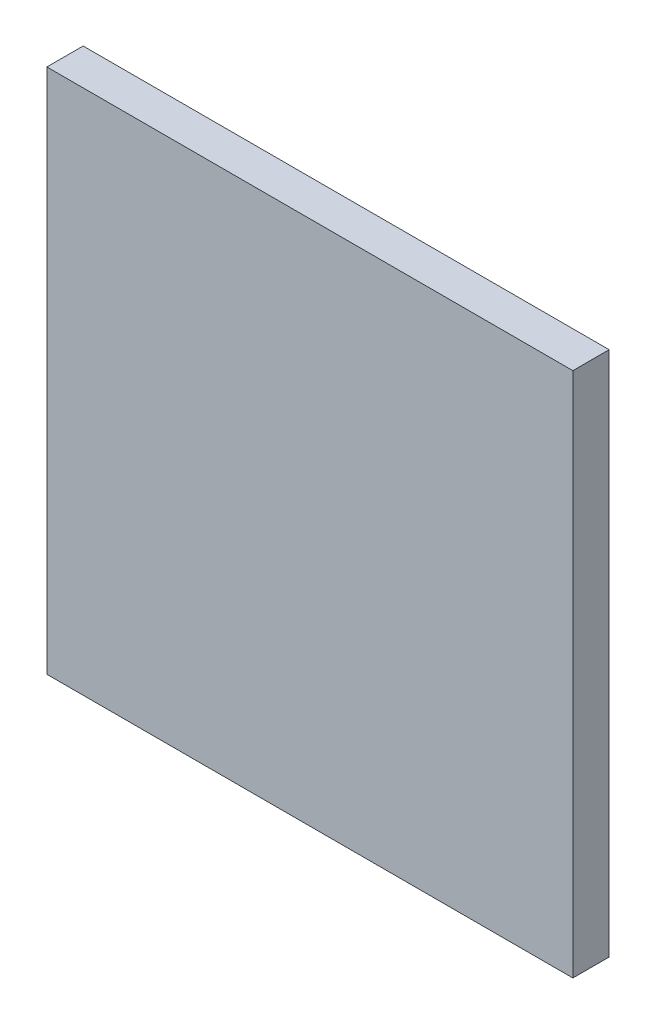
SolidWorks part; units mm, degrees
ref_plane "Front Plane" through (0, 0, 0) normal (0, 0, 1) x (1, 0, 0)
ref_plane "Top Plane" through (0, 0, 0) normal (0, 1, 0) x (1, 0, 0)
ref_plane "Right Plane" through (0, 0, 0) normal (1, 0, 0) x (0, 0, -1)
sketch "Sketch1" plane through (0, 0, 0) normal (0, 0, 1) x (1, 0, 0)
  line L1 (0, 0) -> (14.5, 0)
  line L2 (0, 0) -> (0, 14.5)
  line L3 (0, 14.5) -> (14.5, 14.5)
  line L4 (14.5, 0) -> (14.5, 14.5)
  dimension "D1" = 14.5
  dimension "D2" = 14.5
extrude "Boss-Extrude1" add sketch "Sketch1" along normal blind 1
